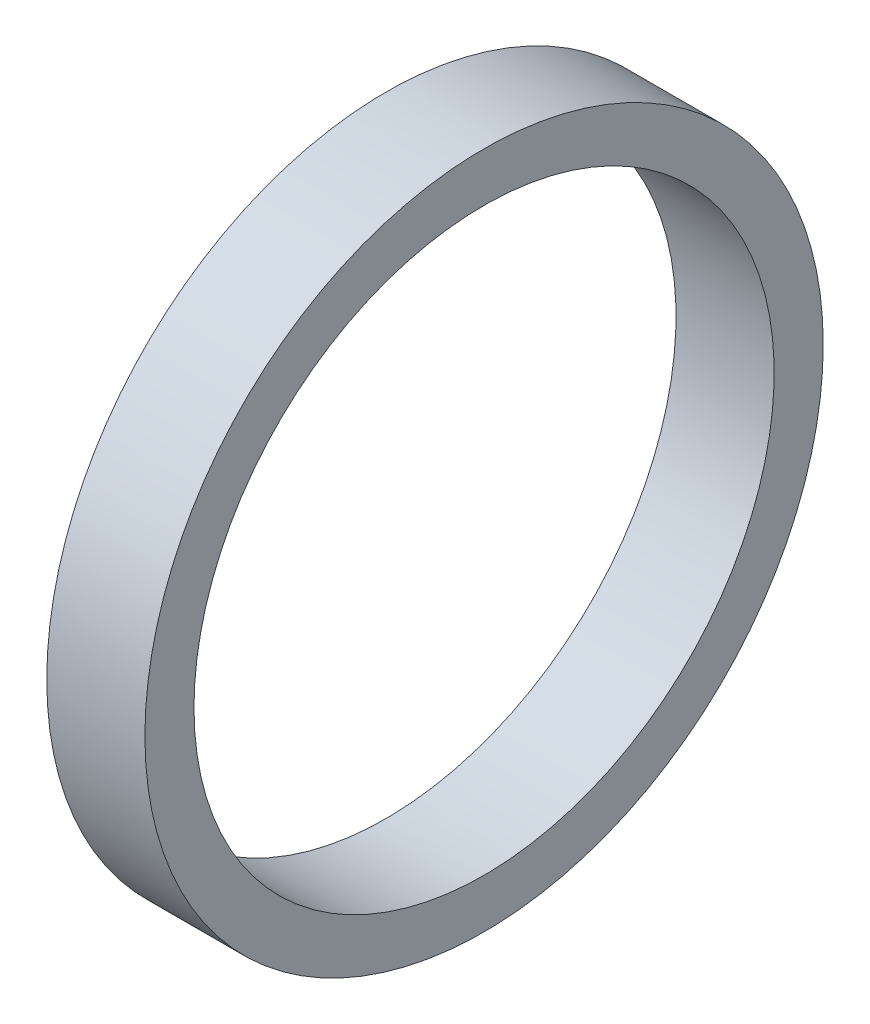
SolidWorks part; units mm, degrees
ref_plane "Face" through (0, 0, 0) normal (0, 0, 1) x (1, 0, 0)
ref_plane "Dessus" through (0, 0, 0) normal (0, 1, 0) x (1, 0, 0)
ref_plane "Droite" through (0, 0, 0) normal (1, 0, 0) x (0, 0, -1)
sketch "Esquisse1" plane through (0, 0, 0) normal (0, 0, 1) x (1, 0, 0)
  line L0 (-74.1441, 0) -> (56.6816, 0) construction
  line L1 (-19.0506, 23.65) -> (-27.0506, 23.65)
  line L2 (-19.0506, 23.65) -> (-19.0506, 27.65)
  line L3 (-19.0506, 27.65) -> (-27.0506, 27.65)
  line L4 (-27.0506, 23.65) -> (-27.0506, 27.65)
  dimension "D1" = 8
  dimension "D2" = 4
  dimension "D3" = 27.65
revolve "Révolution1" add sketch "Esquisse1" angle 360 about L0
